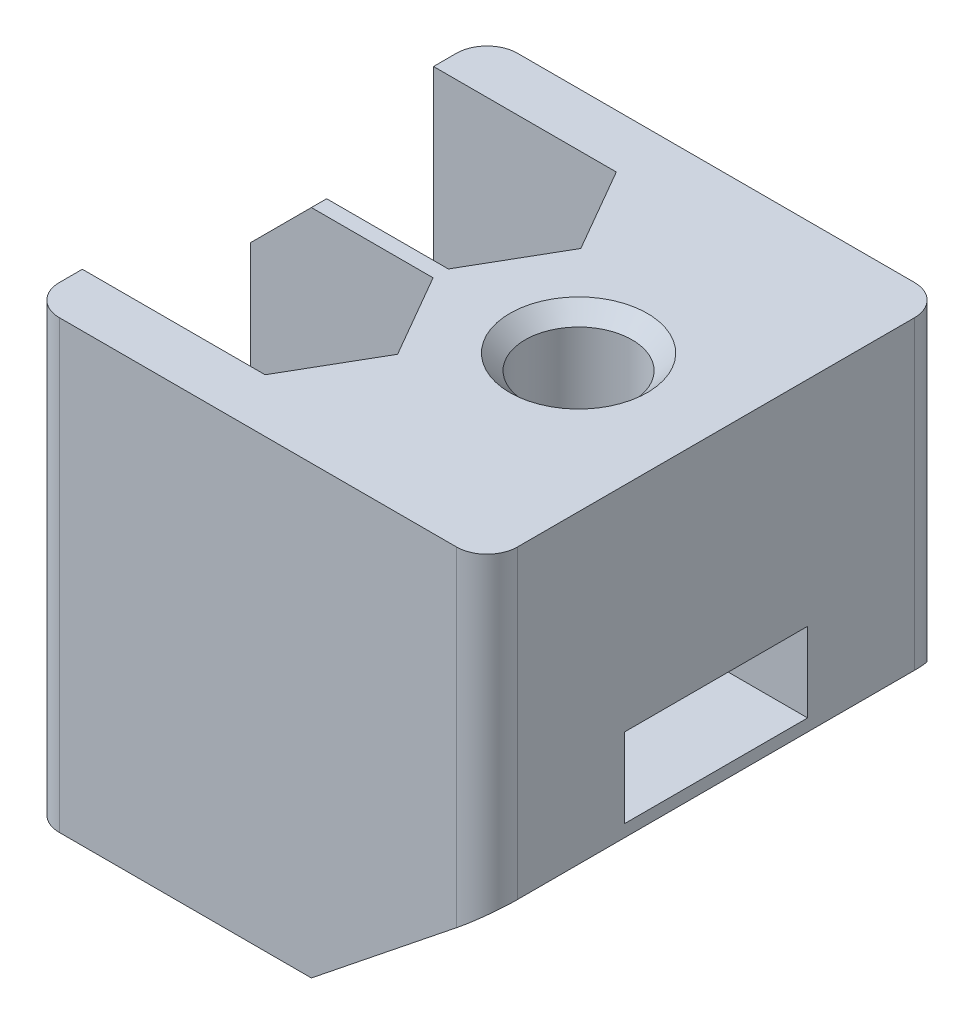
SolidWorks part; units mm, degrees
ref_plane "Front Plane" through (0, 0, 0) normal (0, 0, 1) x (1, 0, 0)
ref_plane "Top Plane" through (0, 0, 0) normal (0, 1, 0) x (1, 0, 0)
ref_plane "Right Plane" through (0, 0, 0) normal (1, 0, 0) x (0, 0, -1)
sketch "Sketch2" plane through (0, 0, 0) normal (0, 1, 0) x (1, 0, 0)
  line L0 (-3.1025, 3) -> (-3.1025, -3) construction
  line L1 (-7.5, 7.5) -> (7.5, 7.5)
  line L2 (-7.5, 7.5) -> (-7.5, 5.75)
  line L3 (-7.5, -7.5) -> (7.5, -7.5)
  line L4 (7.5, 7.5) -> (7.5, 3)
  line L5 (-7.5, 7.5) -> (7.5, -7.5) construction
  line L6 (-7.5, -7.5) -> (7.5, 7.5) construction
  line L7 (0, 0) -> (-3.1025, 0) construction
  line L8 (0, 0) -> (3, 0) construction
  line L9 (-4.6902, 5.75) -> (-7.5, 5.75) construction
  line L10 (0.073, 3) -> (-1.5147, 5.75) construction
  line L11 (-1.5147, 5.75) -> (-4.6902, 5.75) construction
  line L12 (-4.6902, 5.75) -> (-6.2779, 3) construction
  line L13 (-6.2779, 3) -> (-4.6902, 0.25) construction
  line L14 (-4.6902, 0.25) -> (-1.5147, 0.25) construction
  line L15 (-1.5147, 0.25) -> (0.073, 3) construction
  line L16 (0.073, -3) -> (-1.5147, -0.25) construction
  line L17 (-1.5147, -0.25) -> (-4.6902, -0.25) construction
  line L18 (-4.6902, -0.25) -> (-6.2779, -3) construction
  line L19 (-6.2779, -3) -> (-4.6902, -5.75) construction
  line L20 (-4.6902, -5.75) -> (-1.5147, -5.75) construction
  line L21 (-1.5147, -5.75) -> (0.073, -3) construction
  line L22 (6.4641, 0) -> (4.7321, 3) construction
  line L23 (4.7321, 3) -> (1.2679, 3)
  line L24 (1.2679, 3) -> (-0.4641, 0)
  line L25 (-0.4641, 0) -> (1.2679, -3)
  line L26 (1.2679, -3) -> (4.7321, -3)
  line L27 (4.7321, -3) -> (6.4641, 0) construction
  line L28 (-4.6902, 0.25) -> (-7.5, 0.25) construction
  line L29 (-7.5, 0.25) -> (-7.5, -0.25) construction
  line L30 (-4.6902, -0.25) -> (-7.5, -0.25) construction
  line L31 (-4.6902, -5.75) -> (-7.5, -5.75) construction
  line L32 (-7.5, -5.75) -> (-7.5, -7.5)
  line L33 (4.7321, 3) -> (7.5, 3)
  line L34 (4.7321, -3) -> (7.5, -3)
  line L35 (7.5, -3) -> (7.5, -7.5)
  line L36 (3, 0) -> (-3.1025, 3) construction
  line L37 (3, 0) -> (-3.1025, -3) construction
  line L38 (-7.5, 5.75) -> (-7.5, -5.75)
  circle A3 centre (-3.1025, 3) radius 2.75 construction
  circle A4 centre (-3.1025, -3) radius 2.75 construction
  circle A5 centre (3, 0) radius 3 construction
  point P0 (0, 0)
  dimension "D4" = 5.5
  dimension "D5" = 5.5
  dimension "D6" = 6
  dimension "D1" = 15
  dimension "D2" = 15
  dimension "D3" = 6
  dimension "D7" = 6.8
  dimension "D8" = 3
extrude "Boss-Extrude1" add sketch "Sketch2" along normal mid plane 2.6
sketch "Sketch3" plane through (0, 1.3, 0) normal (0, 1, 0) x (1, 0, 0)
  line L1 (7.5, -7.5) -> (-7.5, -7.5)
  line L2 (7.5, -7.5) -> (7.5, 7.5)
  line L3 (7.5, 7.5) -> (-7.5, 7.5)
  line L4 (-7.5, -7.5) -> (-7.5, 7.5)
extrude "Boss-Extrude2" add sketch "Sketch3" along normal blind 5.5
sketch "Sketch5" plane through (0, 6.8, 0) normal (0, 1, 0) x (1, 0, 0)
  circle A0 centre (-3.1025, 3) radius 1.75
  circle A1 centre (-3.1025, -3) radius 1.75
  circle A2 centre (3, 0) radius 1.75
  dimension "D1" = 3.5
  dimension "D2" = 3.5
  dimension "D3" = 3.5
extrude "Cut-Extrude1" cut sketch "Sketch5" against normal through all
sketch "Sketch8" plane through (0, 6.8, 0) normal (0, 1, 0) x (1, 0, 0)
  line L0 (-3.1025, 3) -> (-3.1025, -3) construction
  line L1 (-7.5, 7.5) -> (7.5, 7.5)
  line L2 (-7.5, 7.5) -> (-7.5, 5.75)
  line L3 (-7.5, -7.5) -> (7.5, -7.5)
  line L4 (7.5, 7.5) -> (7.5, 2.75)
  line L5 (-7.5, 7.5) -> (7.5, -7.5) construction
  line L6 (-7.5, -7.5) -> (7.5, 7.5) construction
  line L7 (0, 0) -> (-3.1025, 0) construction
  line L8 (0, 0) -> (3, 0) construction
  line L9 (-4.6902, 5.75) -> (-7.5, 5.75)
  line L10 (0.073, 3) -> (-1.5147, 5.75)
  line L11 (-1.5147, 5.75) -> (-4.6902, 5.75)
  line L12 (-4.6902, 5.75) -> (-6.2779, 3) construction
  line L13 (-6.2779, 3) -> (-4.6902, 0.25) construction
  line L14 (-4.6902, 0.25) -> (-1.5147, 0.25)
  line L15 (-1.5147, 0.25) -> (0.073, 3)
  line L16 (0.073, -3) -> (-1.5147, -0.25)
  line L17 (-1.5147, -0.25) -> (-4.6902, -0.25)
  line L18 (-4.6902, -0.25) -> (-6.2779, -3) construction
  line L19 (-6.2779, -3) -> (-4.6902, -5.75) construction
  line L20 (-4.6902, -5.75) -> (-1.5147, -5.75)
  line L21 (-1.5147, -5.75) -> (0.073, -3)
  line L22 (6.1754, 0) -> (4.5877, 2.75) construction
  line L23 (4.5877, 2.75) -> (1.4123, 2.75) construction
  line L24 (1.4123, 2.75) -> (-0.1754, 0) construction
  line L25 (-0.1754, 0) -> (1.4123, -2.75) construction
  line L26 (1.4123, -2.75) -> (4.5877, -2.75) construction
  line L27 (4.5877, -2.75) -> (6.1754, 0) construction
  line L28 (-4.6902, 0.25) -> (-7.5, 0.25)
  line L29 (-7.5, 0.25) -> (-7.5, -0.25)
  line L30 (-4.6902, -0.25) -> (-7.5, -0.25)
  line L31 (-4.6902, -5.75) -> (-7.5, -5.75)
  line L32 (-7.5, -5.75) -> (-7.5, -7.5)
  line L33 (4.5877, 2.75) -> (7.5, 2.75) construction
  line L34 (4.5877, -2.75) -> (7.5, -2.75) construction
  line L35 (7.5, -2.75) -> (7.5, -7.5)
  line L36 (3, 0) -> (-3.1025, 3) construction
  line L37 (3, 0) -> (-3.1025, -3) construction
  line L38 (7.5, 2.75) -> (7.5, -2.75)
  circle A3 centre (-3.1025, 3) radius 2.75 construction
  circle A4 centre (-3.1025, -3) radius 2.75 construction
  circle A5 centre (3, 0) radius 2.75 construction
  circle A6 centre (3, 0) radius 1.75 construction
  circle A7 centre (3, 0) radius 1.75
  point P0 (0, 0)
  dimension "D4" = 5.5
  dimension "D5" = 5.5
  dimension "D6" = 5.5
  dimension "D1" = 15
  dimension "D2" = 15
  dimension "D3" = 6
  dimension "D7" = 6.8
  dimension "D8" = 3
extrude "Boss-Extrude3" add sketch "Sketch8" along normal blind 1.5
sketch "Sketch9" plane through (0, -1.3, 0) normal (0, -1, 0) x (1, 0, 0)
  line L0 (7.5, 3) -> (7.5, -3)
  line L27 (7.5, 3) -> (7.5, 7.5)
  line L28 (7.5, 7.5) -> (-7.5, 7.5)
  line L29 (-7.5, 7.5) -> (-7.5, -7.5)
  line L30 (-7.5, -7.5) -> (7.5, -7.5)
  line L31 (7.5, -7.5) -> (7.5, -3)
  line L32 (7.5, -3) -> (1.2679, -3)
  line L33 (1.2679, -3) -> (-0.4641, 0)
  line L34 (-0.4641, 0) -> (1.2679, 3)
  line L35 (1.2679, 3) -> (7.5, 3)
  line L36 (7.5, 3) -> (7.5, 7.5)
  line L37 (7.5, 7.5) -> (-7.5, 7.5)
  line L38 (-7.5, 7.5) -> (-7.5, -7.5)
  line L39 (-7.5, -7.5) -> (7.5, -7.5)
  line L40 (7.5, -7.5) -> (7.5, -3)
  circle A0 centre (-3.1025, 3) radius 1.75 construction
  circle A1 centre (-3.1025, 3) radius 1.75
  circle A2 centre (-3.1025, -3) radius 1.75 construction
  circle A3 centre (-3.1025, -3) radius 1.75
  dimension "D1" = 0
extrude "Boss-Extrude4" add sketch "Sketch9" along normal blind 6
sketch "Sketch10" plane through (0, 0, 7.5) normal (0, 0, 1) x (1, 0, 0)
  line L0 (0.5, -7.3) -> (7.5, -1.7)
  line L2 (7.5, -7.3) -> (-7.5, -7.3) construction
  line L3 (7.5, 8.3) -> (7.5, -7.3) construction
  line L4 (7.5, -1.7) -> (7.5, -7.3)
  line L5 (7.5, -7.3) -> (0.5, -7.3)
  dimension "D1" = 3
  dimension "D2" = 8
sketch "Sketch11" plane through (0, 6.8, 0) normal (0, 1, 0) x (1, 0, 0)
  line L25 (-7.5, 0.25) -> (-1.5147, 0.25)
  line L26 (-1.5147, 0.25) -> (0.073, 3)
  line L27 (0.073, 3) -> (-1.5147, 5.75)
  line L28 (-1.5147, 5.75) -> (-7.5, 5.75)
  line L29 (-7.5, 5.75) -> (-7.5, 0.25)
  line L30 (-7.5, 0.25) -> (-1.5147, 0.25)
  line L31 (-1.5147, 0.25) -> (0.073, 3)
  line L32 (0.073, 3) -> (-1.5147, 5.75)
  line L33 (-1.5147, 5.75) -> (-7.5, 5.75)
  line L34 (-7.5, 5.75) -> (-7.5, 0.25)
  line L35 (-7.5, -5.75) -> (-1.5147, -5.75)
  line L36 (-1.5147, -5.75) -> (0.073, -3)
  line L37 (0.073, -3) -> (-1.5147, -0.25)
  line L38 (-1.5147, -0.25) -> (-7.5, -0.25)
  line L39 (-7.5, -0.25) -> (-7.5, -5.75)
  line L40 (-7.5, -5.75) -> (-1.5147, -5.75)
  line L41 (-1.5147, -5.75) -> (0.073, -3)
  line L42 (0.073, -3) -> (-1.5147, -0.25)
  line L43 (-1.5147, -0.25) -> (-7.5, -0.25)
  line L44 (-7.5, -0.25) -> (-7.5, -5.75)
  dimension "D1" = 0
  dimension "D2" = 0
extrude "Cut-Extrude3" cut sketch "Sketch11" against normal offset from surface (4.1 mm away) 10 up to face at (-3.1025, -7.3, 1.25)
extrude "Cut-Extrude4" cut sketch "Sketch10" against normal through all both and the other way through all
chamfer "Chamfer1" distance 0.5 angle 45 1 edges at (3, 8.3, 1.75)
chamfer "Chamfer2" distance 2 angle 45 1 edges at (-7.5, 8.3, 0)
fillet "Fillet1" radius 1 4 edges at (7.5, 3.3, 7.5) (-7.5, 0.5, 7.5) (-7.5, 0.5, -7.5) (7.5, 3.3, -7.5)
chamfer "Chamfer3" distance 1 angle 45 5 edges at (-3, -7.3, -7.5) (-7.2071, -7.3, -7.2071) (-7.5, -7.3, 0) (-7.2071, -7.3, 7.2071) (-3, -7.3, 7.5)
